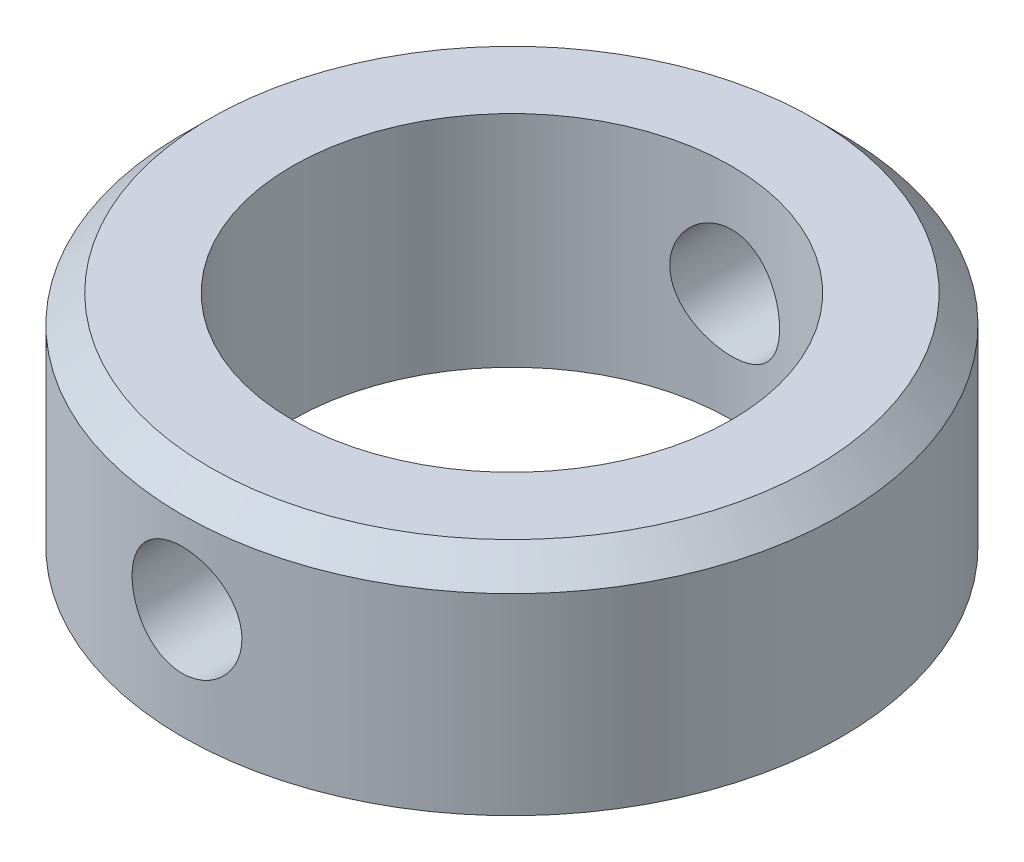
SolidWorks part; units mm, degrees
ref_plane "Front Plane" through (0, 0, 0) normal (0, 0, 1) x (1, 0, 0)
ref_plane "Top Plane" through (0, 0, 0) normal (0, 1, 0) x (1, 0, 0)
ref_plane "Right Plane" through (0, 0, 0) normal (1, 0, 0) x (0, 0, -1)
sketch "Sketch1" plane through (0, 0, 0) normal (0, 1, 0) x (1, 0, 0)
  circle A0 centre (0, 0) radius 12
  circle A1 centre (0, 0) radius 8
  dimension "D1" = 24
  dimension "D2" = 16
extrude "Boss-Extrude1" add sketch "Sketch1" along normal mid plane 8
sketch "Sketch2" plane through (0, 0, 0) normal (0, 0, 1) x (1, 0, 0)
  circle A0 centre (0, 0) radius 2
  dimension "D1" = 4
extrude "Cut-Extrude1" cut sketch "Sketch2" against normal through all both and the other way through all
chamfer "Chamfer1" distance 1 angle 45 1 edges at (0, 4, 12)
